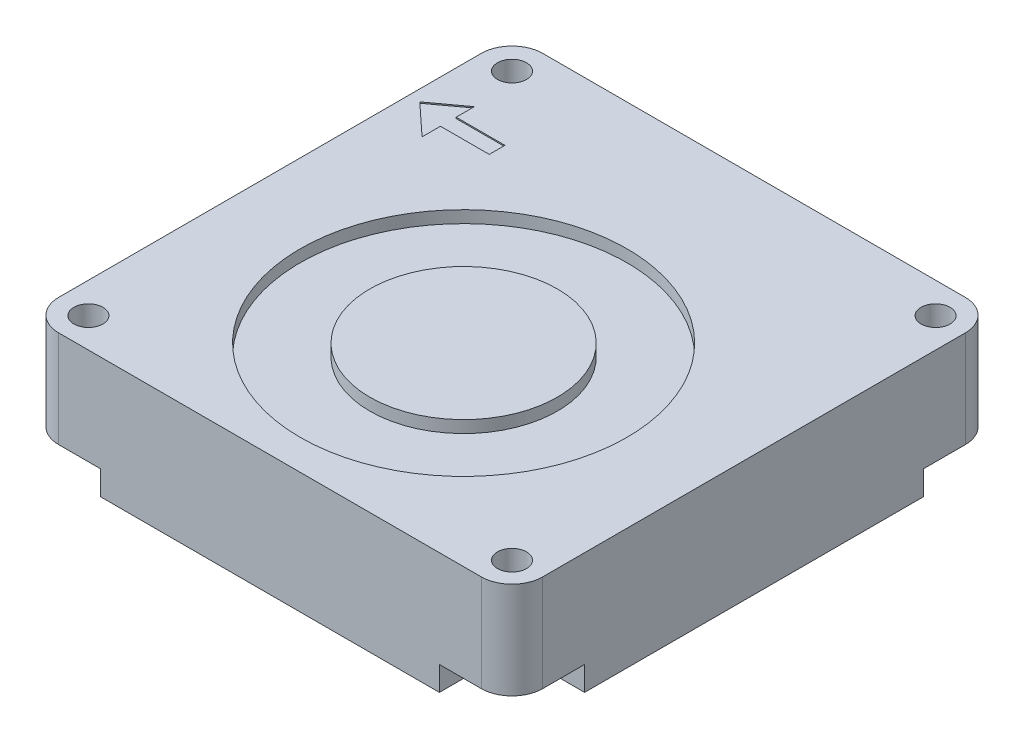
SolidWorks part; units mm, degrees
ref_plane "Front Plane" through (0, 0, 0) normal (0, 0, 1) x (1, 0, 0)
ref_plane "Top Plane" through (0, 0, 0) normal (0, 1, 0) x (1, 0, 0)
ref_plane "Right Plane" through (0, 0, 0) normal (1, 0, 0) x (0, 0, -1)
sketch "Sketch1" plane through (0, 0, 0) normal (0, 1, 0) x (1, 0, 0)
  line L1 (-13.6138, 16.7308) -> (21.3062, 16.7308)
  line L2 (-16.1538, 14.1908) -> (-16.1538, -20.7292)
  line L3 (-13.6138, -23.2692) -> (21.3062, -23.2692)
  line L4 (23.8462, 14.1908) -> (23.8462, -20.7292)
  line L7 (18.8462, 14.1908) -> (18.8462, -20.7292) [skipped]
  line L8 (18.8462, -20.8092) -> (18.8462, -55.7292) [skipped]
  line L9 (-16.1538, -20.8092) -> (-16.1538, -55.7292) [skipped]
  arc A0 (-13.6138, -23.2692) -> (-16.1538, -20.7292) centre (-13.6138, -20.7292) cw
  arc A1 (21.3062, -23.2692) -> (23.8462, -20.7292) centre (21.3062, -20.7292) ccw
  arc A2 (21.3062, 16.7308) -> (23.8462, 14.1908) centre (21.3062, 14.1908) cw
  arc A3 (-16.1538, 14.1908) -> (-13.6138, 16.7308) centre (-13.6138, 14.1908) cw
  circle A4 centre (-13.6138, 14.1908) radius 1.2
  circle A5 centre (21.3862, 14.1908) radius 1.2
  circle A6 centre (21.3862, -20.8092) radius 1.2
  circle A7 centre (-13.6138, -20.8092) radius 1.2
  point P8 (23.8462, -23.2692)
  point P11 (23.8462, 16.7308)
  point P14 (-16.1538, 16.7308)
  dimension "D3" = 2.54
  dimension "D4" = 2
  dimension "D1" = 40
  dimension "D2" = 40
  dimension "D5" = 2
extrude "Boss-Extrude1" add sketch "Sketch1" along normal blind 10
sketch "Sketch3" plane through (0, 10, 0) normal (0, 1, 0) x (1, 0, 0)
  line L0 (-13.6138, -23.2692) -> (21.3062, -23.2692) construction
  line L1 (23.8462, -20.7292) -> (23.8462, 14.1908) construction
  circle A0 centre (3.8462, -7.2692) radius 13.5
  circle A1 centre (3.8462, -7.2692) radius 7.75
  dimension "D1" = 27
  dimension "D2" = 16
  dimension "D3" = 20
extrude "Cut-Extrude1" cut sketch "Sketch3" against normal blind 1
sketch "Sketch4" plane through (-16.1538, 0, 0) normal (-1, 0, 0) x (0, 0, 1)
  line L0 (-16.7308, 10) -> (-16.7308, 0) construction
  line L1 (-10.7308, 0.7172) -> (17.5692, 0.7172)
  line L2 (-10.7308, 0.7172) -> (-10.7308, 9.4672)
  line L3 (-10.7308, 9.4672) -> (17.5692, 9.4672)
  line L4 (17.5692, 0.7172) -> (17.5692, 9.4672)
  dimension "D1" = 8.75
  dimension "D2" = 28.3
  dimension "D3" = 6
extrude "Cut-Extrude2" cut sketch "Sketch4" against normal blind 6.444
sketch "Sketch5" plane through (0, 10, 0) normal (0, 1, 0) x (1, 0, 0)
  line L0 (-12.6258, 10.0929) -> (-12.6258, 8.5892)
  line L1 (-12.6258, 8.5892) -> (-8.5933, 8.5892)
  line L2 (-12.6258, 7.2906) -> (-12.6258, 5.7719)
  line L3 (-12.6258, 7.2906) -> (-8.5933, 7.2906)
  line L4 (-8.5933, 8.5892) -> (-8.5933, 7.2906)
  line L5 (-12.6258, 5.7719) -> (-15.2231, 8.1791)
  line L6 (-15.2231, 8.1791) -> (-12.6258, 10.0929)
extrude "Cut-Extrude3" cut sketch "Sketch5" against normal blind 0.1
sketch "Sketch6" plane through (0, 0, 0) normal (0, -1, 0) x (1, 0, 0)
  line L0 (-16.1538, 17.2692) -> (-13.2018, 17.2692)
  line L1 (-16.1538, -14.1908) -> (-16.1538, 20.7292) construction
  line L2 (-10.1538, 20.3172) -> (-10.1538, 23.2692)
  line L3 (-13.6138, 23.2692) -> (21.3062, 23.2692) construction
  line L4 (23.8462, 17.2692) -> (20.8942, 17.2692)
  line L5 (23.8462, 20.7292) -> (23.8462, -14.1908) construction
  line L6 (17.8462, 20.3172) -> (17.8462, 23.2692)
  line L7 (-10.1538, -16.7308) -> (-10.1538, -13.7788)
  line L8 (21.3062, -16.7308) -> (-13.6138, -16.7308) construction
  line L9 (-13.2018, -10.7308) -> (-16.1538, -10.7308)
  line L10 (17.8462, -16.7308) -> (17.8462, -13.7788)
  line L11 (20.8942, -10.7308) -> (23.8462, -10.7308)
  line L12 (-16.1538, 17.2692) -> (-21.3053, 17.2692)
  line L13 (-21.3053, 17.2692) -> (-21.3053, 27.0613)
  line L14 (-21.3053, 27.0613) -> (-10.1538, 27.0613)
  line L15 (-10.1538, 27.0613) -> (-10.1538, 23.2692)
  line L16 (17.8462, 23.2692) -> (17.8462, 27.0613)
  line L17 (17.8462, 27.0613) -> (26.6688, 27.0613)
  line L18 (26.6688, 27.0613) -> (26.6688, 17.2692)
  line L19 (26.6688, 17.2692) -> (23.8462, 17.2692)
  line L20 (23.8462, -10.7308) -> (26.6688, -10.7308)
  line L21 (26.6688, -10.7308) -> (26.6688, -18.8175)
  line L22 (26.6688, -18.8175) -> (17.8462, -18.8175)
  line L23 (17.8462, -18.8175) -> (17.8462, -16.7308)
  line L24 (-10.1538, -16.7308) -> (-10.1538, -18.8175)
  line L25 (-10.1538, -18.8175) -> (-21.3053, -18.8175)
  line L26 (-21.3053, -18.8175) -> (-21.3053, -10.7308)
  line L27 (-21.3053, -10.7308) -> (-16.1538, -10.7308)
  arc A0 (-13.2018, 17.2692) -> (-10.1538, 20.3172) centre (-13.2018, 20.3172) ccw
  arc A1 (20.8942, 17.2692) -> (17.8462, 20.3172) centre (20.8942, 20.3172) cw
  arc A2 (-10.1538, -13.7788) -> (-13.2018, -10.7308) centre (-13.2018, -13.7788) ccw
  arc A3 (17.8462, -13.7788) -> (20.8942, -10.7308) centre (20.8942, -13.7788) cw
  dimension "D3" = 3.048
  dimension "D5" = 3.048
  dimension "D7" = 3.048
  dimension "D8" = 3.048
  dimension "D1" = 6
  dimension "D2" = 6
  dimension "D4" = 6
  dimension "D6" = 6
extrude "Cut-Extrude4" cut sketch "Sketch6" against normal blind 2
